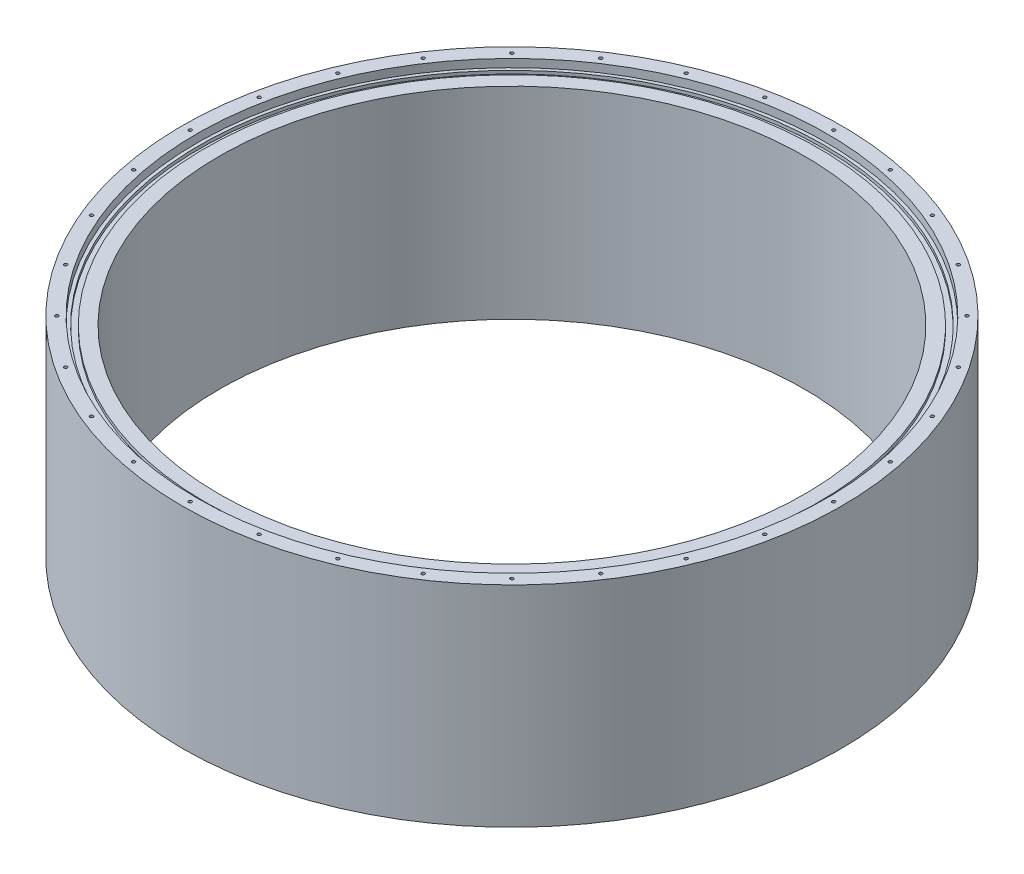
SolidWorks part; units mm, degrees
material "PVC Rigid"
ref_plane "Front" through (0, 0, 0) normal (0, 0, 1) x (1, 0, 0)
ref_plane "Top" through (0, 0, 0) normal (0, 1, 0) x (1, 0, 0)
ref_plane "Right" through (0, 0, 0) normal (1, 0, 0) x (0, 0, -1)
sketch "Sketch1" plane through (0, 0, 0) normal (0, 0, 1) x (1, 0, 0)
  line L0 (225.6, 74.685) -> (243, 74.685)
  line L1 (243, 74.685) -> (243, 80.885)
  line L2 (243, 80.885) -> (254, 80.885)
  line L3 (254, 80.885) -> (254, -80.885)
  line L4 (254, -80.885) -> (225.6, -80.885)
  line L5 (225.6, -80.885) -> (225.6, 74.685)
  line L6 (0, 80.885) -> (0, -80.885) construction
  line L7 (0, 0) -> (225.6, 0) construction
  dimension "D1" = 508
  dimension "D2" = 11
  dimension "D3" = 28.4
  dimension "D4" = 6.2
  dimension "D5" = 161.77
  dimension "D6" = 225.6
  dimension "D7" = 155.57
revolve "Revolve1" add sketch "Sketch1" angle 360 about L6
sketch "Sketch2" plane through (0, 0, 0) normal (0, 0, 1) x (1, 0, 0)
  line L0 (0, 80.885) -> (0, -80.885) construction
  line L1 (254, 80.885) -> (-254, 80.885) construction
  line L2 (-254, -80.885) -> (254, -80.885) construction
  line L3 (240.5, 72.272) -> (240.5, -77.587) construction
  line L4 (236.3344, 74.685) -> (240.5, 74.685)
  line L5 (236.3344, 74.685) -> (236.3344, 72.272)
  line L6 (236.3344, 72.272) -> (240.5, 72.272)
  line L7 (240.5, 74.685) -> (240.5, 72.272)
  line L8 (225.6, 74.685) -> (-225.6, 74.685) construction
  line L9 (225.6, 74.685) -> (-225.6, 74.685) construction
  line L10 (254, -80.885) -> (254, 80.885) construction
  line L12 (236.3344, -78.472) -> (240.5, -78.472) construction
  line L13 (236.3344, -78.472) -> (236.3344, -80.885) construction
  line L14 (236.3344, -80.885) -> (240.5, -80.885) construction
  line L15 (240.5, -78.472) -> (240.5, -80.885) construction
  dimension "D1" = 13.5
  dimension "D2" = 2.413
  dimension "D3" = 4.1656
revolve "Cut-Revolve1" cut sketch "Sketch2" angle 360 about L0
hole_wizard "M3x0.5 Tapped Hole1" positions "Sketch3" profile "Sketch4" tap size "M3x0.5" standard "ANSI Metric"
sketch "Sketch3" plane through (0, 80.885, 0) normal (0, 1, 0) x (1, 0, 0)
  point P0 (248, 0)
  dimension "D1" = 248
sketch "Sketch4" plane through (248, 80.885, 0) normal (1, 0, 0) x (0, 0, 1)
  line L0 (0, 0) -> (0, 10.2511)
  line L1 (0, 10.2511) -> (1.25, 9.5)
  line L2 (1.25, 9.5) -> (1.25, 0)
  line L5 (1.25, 0) -> (0, 0)
  line L10 (0, 10.2511) -> (-1.25, 9.5) construction
  line L11 (0, -6.35) -> (0, 107.95) construction
  dimension "Tap Drill Dia." = 2.5
  dimension "Tap Drill Depth" = 9.5
  dimension "Drill Angle" = 118
cosmetic thread "Hole Thread1" parameters "D1"=8, "D2"=3
pattern_circular "CirPattern1" count 32 over 360 about axis through (0, 0, 0) along (0, 1, 0) of "M3x0.5 Tapped Hole1"
mirror "Mirror1" about plane through (0, 0, 0) normal (0, 1, 0) of "CirPattern1", "M3x0.5 Tapped Hole1"
hole_wizard "Ø5.0mm Dowel Hole1" positions "Sketch5" profile "Sketch6" hole size "Ø5.0" standard "ANSI Metric"
sketch "Sketch5" plane through (0, -80.885, 0) normal (0, -1, 0) x (-1, 0, 0)
  line L2 (0, 0) -> (0, 204.5498) construction
  line L3 (-24.2102, 245.8106) -> (0, 0) construction
  line L4 (0, 0) -> (24.9245, -253.0623) construction
  circle A1 centre (0, 0) radius 247
  point P6 (-24.2102, 245.8106)
  point P8 (24.2102, -245.8106)
  dimension "D2" = 494
  dimension "D1" = 5.625
sketch "Sketch6" plane through (-24.2102, -80.885, 245.8106) normal (1, 0, 0) x (0, 0, -1)
  line L0 (0, 0) -> (0, 7.5172)
  line L1 (0, 7.5172) -> (2.525, 6)
  line L2 (2.525, 6) -> (2.525, 0)
  line L5 (2.525, 0) -> (0, 0)
  line L10 (0, 7.5172) -> (-2.525, 6) construction
  line L11 (0, -6.35) -> (0, 107.95) construction
  dimension "Hole Dia." = 5.05
  dimension "Hole Depth" = 6
  dimension "Drill Angle" = 118
